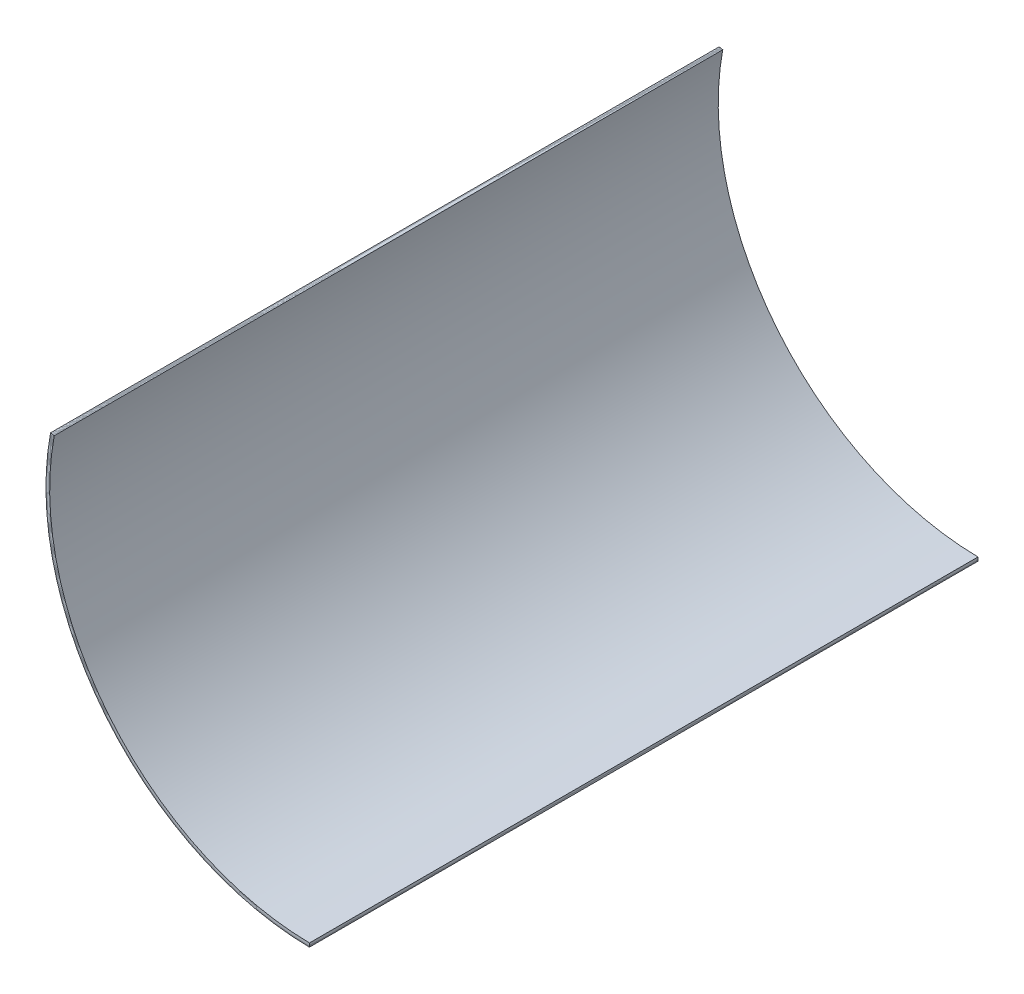
SolidWorks part; units mm, degrees
ref_plane "Front Plane" through (0, 0, 0) normal (0, 0, 1) x (1, 0, 0)
ref_plane "Top Plane" through (0, 0, 0) normal (0, 1, 0) x (1, 0, 0)
ref_plane "Right Plane" through (0, 0, 0) normal (1, 0, 0) x (0, 0, -1)
sketch "Sketch1" plane through (0, 0, 0) normal (0, 0, 1) x (1, 0, 0)
  arc A0 (-2.8844, -241.2828) -> (-237.1163, 44.7389) centre (0, 0) cw
  arc A1 (-2.8941, -242.0955) -> (-237.915, 44.8896) centre (0, 0) cw
  dimension "D1" = 0.8128
  dimension "D2" = 241.3
extrude "Extrude-Thin1" add sketch "Sketch1" along normal blind 607.06 thin
